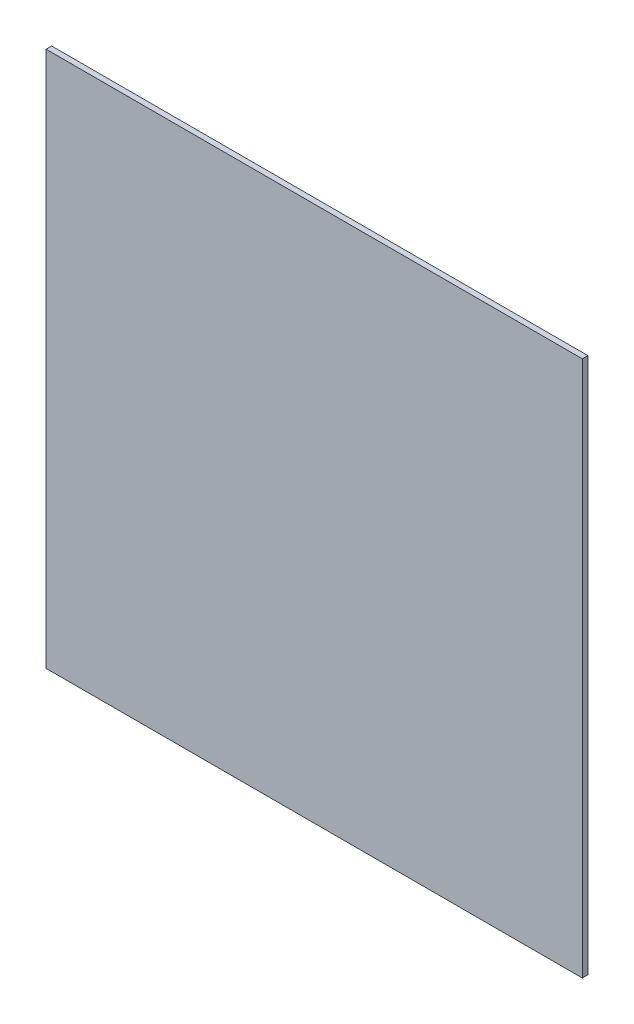
SolidWorks part; units mm, degrees
material "Alloy Steel"
ref_plane "Front Plane" through (0, 0, 0) normal (0, 0, 1) x (1, 0, 0)
ref_plane "Top Plane" through (0, 0, 0) normal (0, 1, 0) x (1, 0, 0)
ref_plane "Right Plane" through (0, 0, 0) normal (1, 0, 0) x (0, 0, -1)
sketch "Sketch1" plane through (0, 0, 0) normal (0, 0, 1) x (1, 0, 0)
  line L1 (0, -5189) -> (-914.4, -5189)
  line L2 (0, -5189) -> (0, -4274.6)
  line L3 (0, -4274.6) -> (-914.4, -4274.6)
  line L4 (-914.4, -5189) -> (-914.4, -4274.6)
  dimension "D1" = 914.4
  dimension "D2" = 914.4
extrude "Boss-Extrude1" add sketch "Sketch1" along normal blind 9.525
